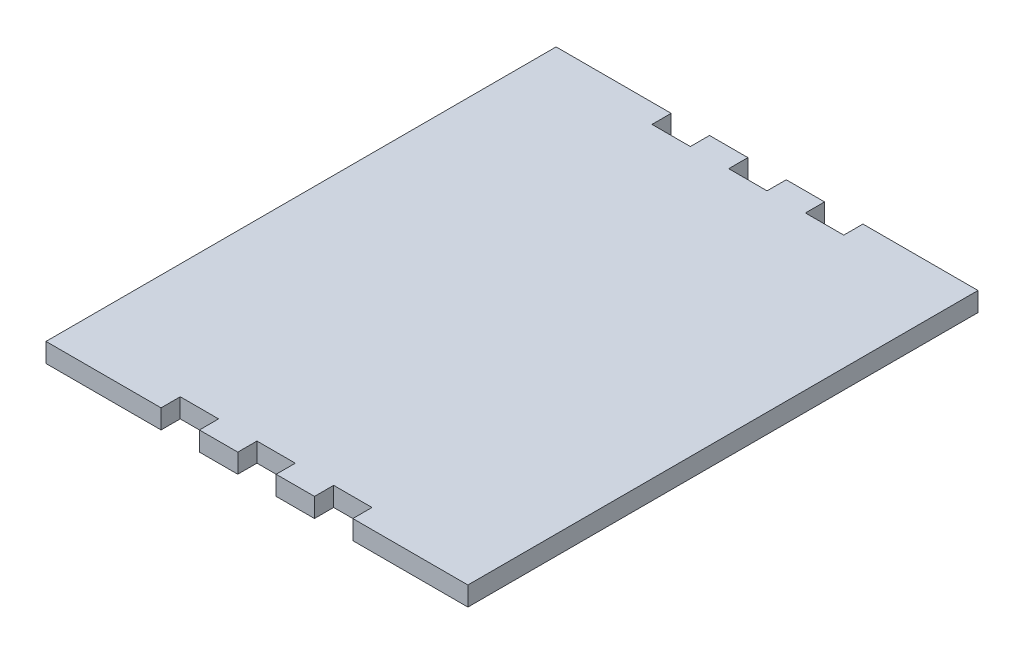
SolidWorks part; units mm, degrees
ref_plane "Front Plane" through (0, 0, 0) normal (0, 0, 1) x (1, 0, 0)
ref_plane "Top Plane" through (0, 0, 0) normal (0, 1, 0) x (1, 0, 0)
ref_plane "Right Plane" through (0, 0, 0) normal (1, 0, 0) x (0, 0, -1)
sketch "Sketch1" plane through (0, 0, 0) normal (0, 1, 0) x (1, 0, 0)
  line L0 (-34.925, -42.2275) -> (-15.875, -42.2275)
  line L1 (-34.925, -42.2275) -> (34.925, -42.2275) construction
  line L2 (-34.925, -42.2275) -> (-34.925, 42.2275)
  line L3 (-34.925, 42.2275) -> (34.925, 42.2275) construction
  line L4 (34.925, -42.2275) -> (34.925, 42.2275)
  line L5 (-34.925, -42.2275) -> (34.925, 42.2275) construction
  line L6 (-34.925, 42.2275) -> (34.925, -42.2275) construction
  line L7 (-15.875, -42.2275) -> (-15.875, -39.0525)
  line L8 (-15.875, -39.0525) -> (-9.525, -39.0525)
  line L9 (-9.525, -39.0525) -> (-9.525, -42.2275)
  line L10 (-9.525, -42.2275) -> (-3.175, -42.2275)
  line L11 (-3.175, -42.2275) -> (-3.175, -39.0525)
  line L12 (-3.175, -39.0525) -> (3.175, -39.0525)
  line L13 (3.175, -39.0525) -> (3.175, -42.2275)
  line L14 (15.875, -42.2275) -> (34.925, -42.2275)
  line L15 (15.875, -42.2275) -> (15.875, -39.0525)
  line L16 (15.875, -39.0525) -> (9.525, -39.0525)
  line L17 (9.525, -39.0525) -> (9.525, -42.2275)
  line L18 (9.525, -42.2275) -> (3.175, -42.2275)
  line L19 (9.525, 39.0525) -> (9.525, 42.2275)
  line L20 (34.925, 0) -> (-34.925, 0) construction
  line L21 (15.875, 39.0525) -> (9.525, 39.0525)
  line L22 (15.875, 42.2275) -> (15.875, 39.0525)
  line L23 (3.175, 39.0525) -> (3.175, 42.2275)
  line L24 (-3.175, 39.0525) -> (3.175, 39.0525)
  line L25 (-3.175, 42.2275) -> (-3.175, 39.0525)
  line L26 (-9.525, 42.2275) -> (-3.175, 42.2275)
  line L27 (-9.525, 39.0525) -> (-9.525, 42.2275)
  line L28 (-15.875, 39.0525) -> (-9.525, 39.0525)
  line L29 (-15.875, 42.2275) -> (-15.875, 39.0525)
  line L30 (-34.925, 42.2275) -> (-15.875, 42.2275)
  line L31 (3.175, 42.2275) -> (9.525, 42.2275)
  line L32 (15.875, 42.2275) -> (34.925, 42.2275)
  point P0 (0, 0)
  dimension "D1" = 69.85
  dimension "D2" = 84.455
  dimension "D3" = 19.05
  dimension "D4" = 6.35
  dimension "D5" = 6.35
  dimension "D6" = 6.35
  dimension "D7" = 3.175
  dimension "D8" = 6.35
  dimension "D9" = 3.175
  dimension "D10" = 3.175
extrude "Boss-Extrude1" add sketch "Sketch1" along normal blind 3.175 contours L28 L27 L26 L25 L24 L23 L31 L19 L21 L22 L32 L4 L14 L15 L16 L17 L18 L13 L12 L11 L10 L9 L8 L7 L0 L2 L30 L29
